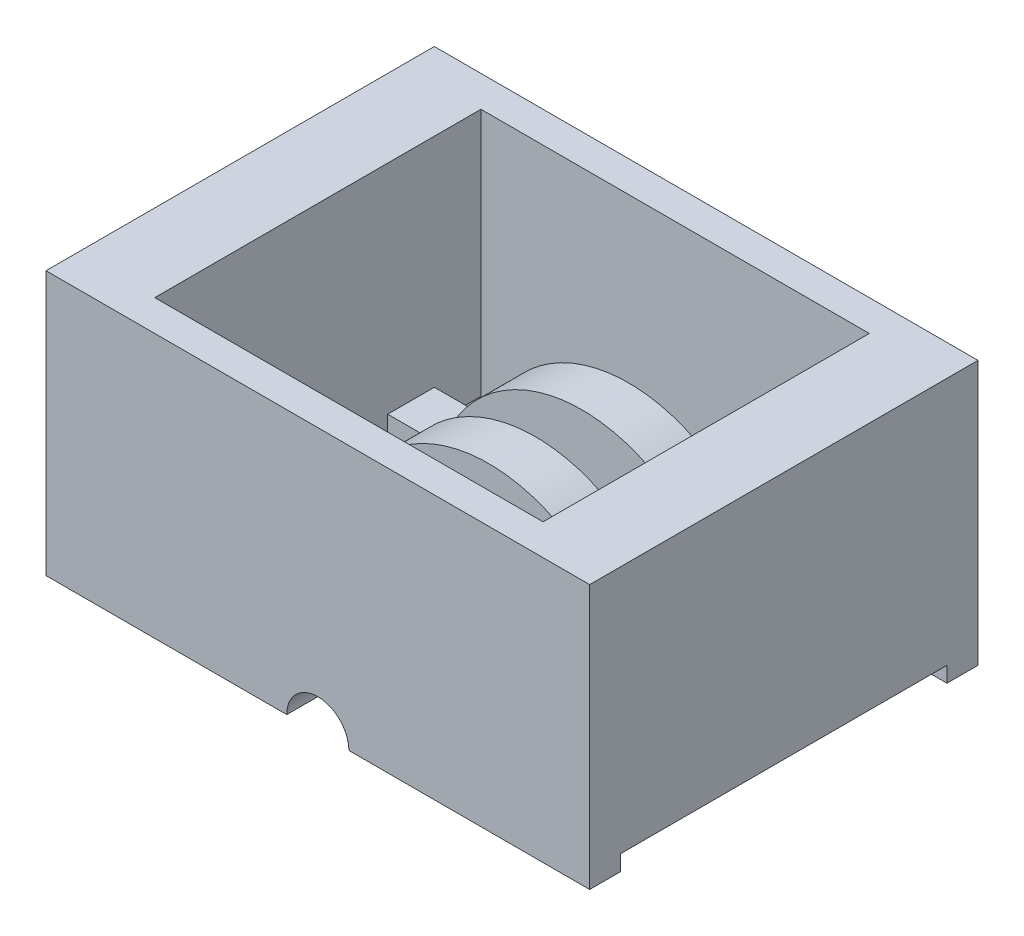
SolidWorks part; units mm, degrees
ref_plane "Front Plane" through (0, 0, 0) normal (0, 0, 1) x (1, 0, 0)
ref_plane "Top Plane" through (0, 0, 0) normal (0, 1, 0) x (1, 0, 0)
ref_plane "Right Plane" through (0, 0, 0) normal (1, 0, 0) x (0, 0, -1)
sketch "Sketch1" plane through (0, 0, 0) normal (0, 0, 1) x (1, 0, 0)
  line L0 (-167.812, 0) -> (167.812, 0) construction
  line L1 (0, -200.8824) -> (0, 200.8824) construction
  line L2 (125, -214.475) -> (125, 214.475) construction
  line L3 (125, 0) -> (125, 150) construction
  line L4 (20, 0) -> (125, 0)
  line L5 (125, 150) -> (-125, 150) construction
  line L6 (-125, 0) -> (-125, 150) construction
  line L7 (-20, 0) -> (-125, 0)
  line L8 (-175, 0) -> (-175, 170)
  line L9 (-175, 170) -> (175, 170)
  line L10 (175, 170) -> (175, 0)
  line L11 (-175, 0) -> (-125, 0)
  line L12 (175, 0) -> (125, 0)
  circle A1 centre (0, 0) radius 100 construction
  circle A2 centre (0, 0) radius 125 construction
  arc A3 (20, 0) -> (-20, 0) centre (0, 0) ccw
  point P4 (0, 0)
  point P8 (0, 0)
  point P14 (125, 0)
  point P20 (0, 150)
  dimension "D1" = 40
  dimension "D2" = 200
  dimension "D3" = 125
  dimension "D5" = 150
  dimension "D6" = 170
  dimension "D7" = 175
  dimension "D8" = 175
  dimension "D4" = 25
extrude "Boss-Extrude1" add sketch "Sketch1" along normal mid plane 250
sketch "Sketch4" plane through (0, 170, 0) normal (0, 1, 0) x (1, 0, 0)
  line L0 (-279.8336, 0) -> (279.8336, 0) construction
  line L2 (0, -200.6202) -> (0, 200.6202) construction
  line L3 (125, -196.7043) -> (125, 196.7043) construction
  line L4 (-245.0805, 105) -> (245.0805, 105) construction
  line L5 (-125, 105) -> (125, 105)
  line L6 (125, 105) -> (125, -105)
  line L7 (-125, -105) -> (125, -105)
  line L8 (-125, 105) -> (-125, -105)
  point P3 (0, 0)
  point P7 (0, 0)
  point P10 (125, 0)
  point P13 (0, 105)
  point P17 (125, 0)
  point P19 (0, -105)
  point P20 (0, 105)
  dimension "D1" = 125
  dimension "D2" = 105
extrude "Cut-Extrude2" cut sketch "Sketch4" against normal blind 250
sketch "Sketch3" plane through (0, 0, 0) normal (0, 0, 1) x (1, 0, 0)
  line L0 (-176.8816, 0) -> (176.8816, 0) construction
  line L1 (0, -186.9875) -> (0, 186.9875) construction
  line L2 (125, 0) -> (125, 30)
  line L3 (-238.8935, 95) -> (238.8935, 95) construction
  line L6 (125, 0) -> (125, 95) construction
  line L7 (125, 95) -> (-125, 95) construction
  line L8 (-125, 30) -> (-125, 0)
  line L9 (-174.3553, 30) -> (174.3553, 30) construction
  line L10 (-90.1388, 30) -> (-125, 30)
  line L11 (90.1388, 30) -> (125, 30)
  line L12 (-125, 0) -> (-20, 0)
  line L13 (20, 0) -> (125, 0)
  arc A0 (20, 0) -> (-20, 0) centre (0, 0) ccw
  circle A1 centre (0, 0) radius 100 construction
  circle A3 centre (0, 0) radius 125 construction
  arc A4 (90.1388, 30) -> (-90.1388, 30) centre (0, 0) ccw
  point P7 (0, 0)
  point P9 (0, 0)
  point P15 (125, 0)
  point P17 (0, 95)
  point P28 (0, 30)
  dimension "D1" = 200
  dimension "D2" = 95
  dimension "D4" = 30
extrude "Boss-Extrude2" add sketch "Sketch3" along normal mid plane 30
pattern_linear "LPattern1" count 2 spacing 60 along (0, 0, 1) count 2 spacing 60 along (0, 0, -1) of "Boss-Extrude2"
sketch "Sketch5" plane through (175, 0, 0) normal (1, 0, 0) x (0, 0, -1)
  line L0 (-224.3226, 0) -> (224.3226, 0) construction
  line L2 (0, -305.9145) -> (0, 305.9145) construction
  line L3 (-105, 0) -> (105, 0)
  line L4 (105, 0) -> (105, 10)
  line L5 (105, 10) -> (-105, 10)
  line L6 (-105, 0) -> (-105, 10)
  point P4 (0, 0)
  point P8 (0, 0)
  point P12 (0, 0)
  point P14 (0, 10)
  dimension "D1" = 10
  dimension "D2" = 210
extrude "Cut-Extrude3" cut sketch "Sketch5" against normal blind 65
sketch "Sketch6" plane through (-175, 0, 0) normal (-1, 0, 0) x (0, 0, 1)
  line L0 (-187.3386, 0) -> (187.3386, 0) construction
  line L2 (0, -228.0673) -> (0, 228.0673) construction
  line L3 (-105, 0) -> (105, 0)
  line L4 (105, 0) -> (105, 10)
  line L5 (105, 10) -> (-105, 10)
  line L6 (-105, 0) -> (-105, 10)
  point P0 (0, 10)
  point P4 (0, 0)
  point P8 (0, 0)
  point P14 (0, 0)
  dimension "D1" = 10
  dimension "D2" = 105
extrude "Cut-Extrude4" cut sketch "Sketch6" against normal blind 65
